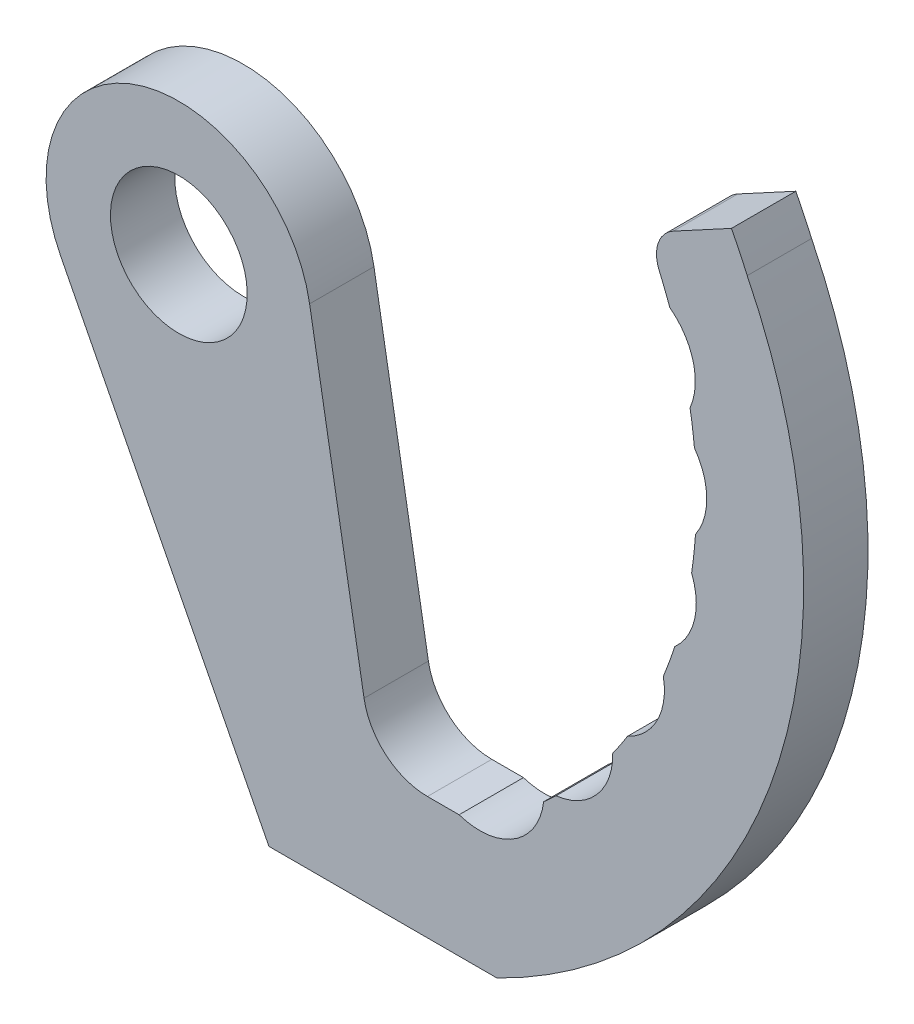
SolidWorks part; units mm, degrees
ref_plane "Plan de face" through (0, 0, 0) normal (0, 0, 1) x (1, 0, 0)
ref_plane "Plan de dessus" through (0, 0, 0) normal (0, 1, 0) x (1, 0, 0)
ref_plane "Plan de droite" through (0, 0, 0) normal (1, 0, 0) x (0, 0, -1)
sketch "Esquisse1" plane through (0, 0, 0) normal (0, 0, 1) x (1, 0, 0)
  circle A0 centre (22.626, -8.5) radius 2.125
  circle A1 centre (22.626, -8.5) radius 4.125
  dimension "D1" = 4.25
  dimension "D2" = 2
extrude "Boss.-Extru.1" add sketch "Esquisse1" along normal up to surface (2 mm away)
sketch "Esquisse2" plane through (0, 0, 2) normal (0, 0, 1) x (1, 0, 0)
  line L0 (31.626, -19.2238) -> (31.626, 2.2238) construction
  line L1 (30.5098, -23.03) -> (25.4261, -23.03)
  line L2 (37.1601, -0.6386) -> (39.7989, 0.7887)
  line L3 (22.626, -8.5) -> (37.1601, -0.6386) construction
  line L4 (25.4261, -23.03) -> (18.9537, -10.3788)
  line L5 (31.626, -19.2238) -> (28.6684, -19.2238)
  line L6 (28.6684, -19.2238) -> (26.6905, -7.7965)
  line L7 (25.4261, -23.03) -> (28.6684, -19.2238) construction
  arc A0 (31.626, -19.2238) -> (31.626, 2.2238) centre (22.626, -8.5) ccw construction
  circle A1 centre (22.626, -8.5) radius 2.125 construction
  arc A3 (31.626, -19.2238) -> (37.1601, -0.6386) centre (24.714, -7.049) ccw
  circle A4 centre (36.626, -8.5) radius 2 construction
  arc A5 (39.7989, 0.7887) -> (30.5098, -23.03) centre (24.714, -7.049) cw
  circle A6 centre (22.626, -8.5) radius 4.125 construction
  arc A7 (26.6905, -7.7965) -> (18.9537, -10.3788) centre (22.626, -8.5) cw
  point P7 (36.626, -8.5)
  dimension "D1" = 5
  dimension "D2" = 3
  dimension "D3" = 5
extrude "Boss.-Extru.2" add sketch "Esquisse2" against normal up to surface (2 mm away) up to face at (26.751, -8.5, 0)
sketch "Esquisse3" plane through (0, 0, 2) normal (0, 0, 1) x (1, 0, 0)
  line L0 (28.6684, -19.2238) -> (26.6905, -7.7965) construction
  line L1 (31.626, -19.2238) -> (28.6684, -19.2238) construction
  arc A0 (28.6684, -19.2238) -> (35.5804, -0.9203) centre (23.8278, -6.939) ccw construction
  arc A1 (38.1674, -5.2262) -> (35.5403, -5.54) centre (36.6759, -3.8937) ccw
  arc A2 (35.5403, -5.54) -> (35.5538, -8.22) centre (37.0317, -6.8725) ccw
  arc A3 (35.5538, -8.22) -> (34.962, -10.8339) centre (36.7059, -9.8548) ccw
  arc A4 (34.962, -10.8339) -> (33.7954, -13.2467) centre (35.7154, -12.6865) ccw
  arc A5 (33.7954, -13.2467) -> (32.1143, -15.3339) centre (34.1111, -15.2216) ccw
  arc A6 (32.1143, -15.3339) -> (33.9729, -17.2168) centre (31.9761, -17.3291) ccw
  arc A7 (38.1839, -8.5073) -> (38.1674, -5.2262) centre (37.0317, -6.8725) ccw
  arc A8 (37.4593, -11.7075) -> (38.1839, -8.5073) centre (36.7059, -9.8548) ccw
  arc A9 (36.0311, -14.6615) -> (37.4593, -11.7075) centre (35.7154, -12.6865) ccw
  arc A10 (33.9729, -17.2168) -> (36.0311, -14.6615) centre (34.1111, -15.2216) ccw
  point P3 (36.6759, -3.8937)
  dimension "D1" = 4
  dimension "D2" = 3
  dimension "D3" = 3
  dimension "D4" = 3
  dimension "D5" = 3
  dimension "D6" = 3
extrude "Enlèv. mat.-Extru.1" cut sketch "Esquisse3" against normal through all
sketch "Esquisse4" plane through (0, 0, 2) normal (0, 0, 1) x (1, 0, 0)
  line L0 (30.5098, -23.03) -> (32.5098, -23.03)
  arc A0 (32.5098, -23.03) -> (40.2893, -0.2378) centre (25.0436, -7.7579) ccw
  arc A1 (30.5098, -23.03) -> (39.7989, 0.7887) centre (24.714, -7.049) ccw construction
  arc A2 (30.5098, -23.03) -> (40.2893, -0.2378) centre (24.714, -7.049) ccw
  dimension "D1" = 2
extrude "Boss.-Extru.3" add sketch "Esquisse4" against normal up to surface (2 mm away) up to face at (34.41, -11.5349, 0)
fillet "Congé1" radius 1 1 edges at (37.1601, -0.6386, 1)
fillet "Congé2" radius 2 1 edges at (28.6684, -19.2238, 1)
